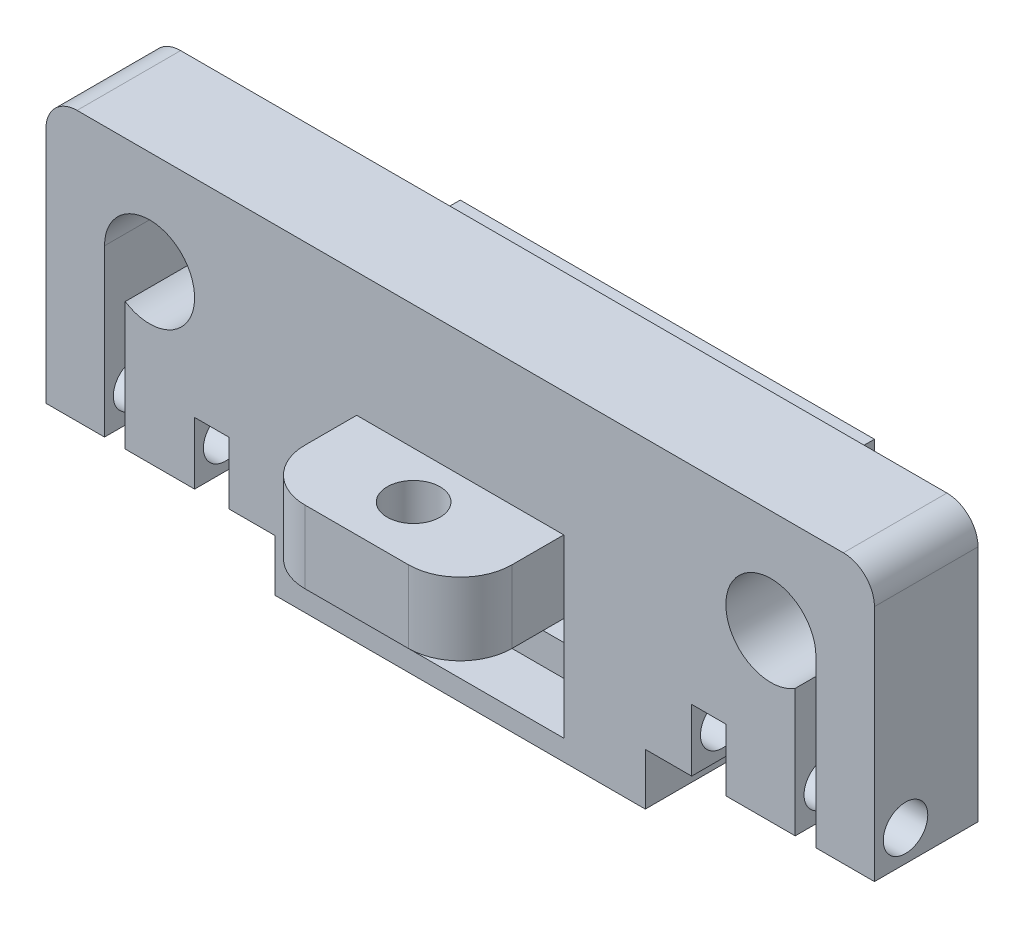
SolidWorks part; units mm, degrees
ref_plane "Front Plane" through (0, 0, 0) normal (0, 0, 1) x (1, 0, 0)
ref_plane "Top Plane" through (0, 0, 0) normal (0, 1, 0) x (1, 0, 0)
ref_plane "Right Plane" through (0, 0, 0) normal (1, 0, 0) x (0, 0, -1)
sketch "Sketch1" plane through (0, 0, 0) normal (0, 0, 1) x (1, 0, 0)
  line L0 (0, -16.0288) -> (0, 16.9064) construction
  line L1 (40, -13) -> (34.35, -13)
  line L2 (40, -13) -> (40, 13)
  line L3 (40, 13) -> (-40, 13)
  line L4 (-40, -13) -> (-40, 13)
  line L5 (40, -13) -> (34.35, -11.1638) construction
  line L6 (40, 13) -> (-32.35, -10.5138) construction
  line L7 (5.1, -6) -> (5.1, -13)
  line L8 (-7.5, -6) -> (-5.1, -6)
  line L9 (-7.5, -6) -> (-7.5, -13)
  line L11 (-5.1, -6) -> (-5.1, -13)
  line L12 (-7.5, -6) -> (-5.1, -13) construction
  line L13 (-7.5, -13) -> (-5.1, -6) construction
  line L14 (7.5, -6) -> (7.5, -13)
  line L15 (7.5, -6) -> (5.1, -6)
  line L16 (-7.5, -13) -> (-32.35, -13)
  line L17 (5.1, -13) -> (-5.1, -13)
  line L18 (-34.35, -13) -> (-40, -13)
  line L20 (-34.35, 3) -> (-34.35, -13)
  line L22 (-32.35, -0.6606) -> (-32.35, -13)
  line L23 (-34.35, -11.1638) -> (-40, -13) construction
  line L24 (32.35, -0.6606) -> (32.35, -13)
  line L25 (34.35, 3) -> (34.35, -13)
  line L26 (32.35, -13) -> (7.5, -13)
  line L27 (32.35, -10.5137) -> (-40, 13) construction
  arc A0 (-32.35, -0.6606) -> (-34.35, 3) centre (-30, 3) ccw
  arc A2 (32.35, -0.6606) -> (34.35, 3) centre (30, 3) cw
  point P0 (0, 0)
  point P13 (-6.3, -9.5)
  point P31 (-32.35, -6.8303)
  dimension "D3" = 8.7
  dimension "D1" = 80
  dimension "D2" = 26
  dimension "D4" = 10
  dimension "D5" = 10
  dimension "D6" = 7
  dimension "D7" = 2.4
  dimension "D8" = 6.3
  dimension "D9" = 2
extrude "Boss-Extrude1" add sketch "Sketch1" along normal mid plane 10
sketch "Sketch2" plane through (0, 0, 5) normal (0, 0, 1) x (1, 0, 0)
  line L5 (-40, 13) -> (-40, -13) construction
  line L6 (-25.65, -13) -> (-22.35, -13)
  line L7 (-25.65, -13) -> (-25.65, -7)
  line L8 (-25.65, -7) -> (-22.35, -7)
  line L9 (-22.35, -13) -> (-22.35, -7)
  line L10 (-25.65, -13) -> (-22.35, -7) construction
  line L11 (-25.65, -7) -> (-22.35, -13) construction
  line L12 (-32.35, -13) -> (-7.5, -13) construction
  line L13 (0, -16.0948) -> (0, 19.1324) construction
  line L14 (22.35, -13) -> (22.35, -7)
  line L15 (25.65, -13) -> (25.65, -7)
  line L16 (25.65, -7) -> (22.35, -7)
  line L17 (25.65, -13) -> (22.35, -13)
  point P0 (-24, -10)
  point P7 (-24, -13)
  dimension "D1" = 16
  dimension "D2" = 3.3
  dimension "D4" = 0
  dimension "D5" = 3
extrude "Cut-Extrude2" cut sketch "Sketch2" against normal blind 6.5 contours L7 L6 L9 L8 | L17 L14 L16 L15
sketch "Sketch3" plane through (-40, 0, 0) normal (-1, 0, 0) x (0, 0, 1)
  line L0 (5, -13) -> (-5, -13) construction
  line L1 (-5, 13) -> (-5, -13) construction
  circle A0 centre (2, -10) radius 2.15
  dimension "D1" = 4.3
  dimension "D2" = 3
  dimension "D3" = 7
extrude "Cut-Extrude4" cut sketch "Sketch3" against normal blind 24
mirror "Mirror1" about plane through (0, 0, 0) normal (1, 0, 0) of "Cut-Extrude4"
fillet "Fillet1" radius 0.5 2 edges at (5.1, -9.5, -5) (-5.1, -9.5, -5)
fillet "Fillet2" radius 3 2 edges at (40, 13, 0) (-40, 13, 0)
sketch "Sketch5" plane through (0, 0, 5) normal (0, 0, 1) x (1, 0, 0)
  line L2 (-5.1, -6) -> (5.1, -6)
  line L3 (-5.1, -6) -> (-5.1, -13)
  line L4 (-5.1, -13) -> (5.1, -13)
  line L5 (5.1, -6) -> (5.1, -13)
  line L6 (-5.1, -6) -> (5.1, -13) construction
  line L7 (-5.1, -13) -> (5.1, -6) construction
  point P2 (0, -9.5)
  dimension "D1" = 7
extrude "Cut-Extrude5" cut sketch "Sketch5" against normal through all
sketch "Sketch8" plane through (0, 0, -5) normal (0, 0, -1) x (-1, 0, 0)
  line L6 (32.35, -13) -> (7.5, -13) construction
  line L7 (-10, -6) -> (10, -6)
  line L8 (-10, -6) -> (-10, -13)
  line L9 (-10, -13) -> (10, -13)
  line L10 (10, -6) -> (10, -13)
  line L11 (-10, -6) -> (10, -13) construction
  line L12 (-10, -13) -> (10, -6) construction
  line L13 (-7.5, -6) -> (-7.5, -13) construction
  line L17 (7.5, -13) -> (7.5, -6) construction
  point P0 (0, -9.5)
  dimension "D1" = 20
  dimension "D2" = 2.5
  dimension "D3" = 2.5
  dimension "D4" = 7
extrude "Cut-Extrude6" cut sketch "Sketch8" against normal through all
sketch "Sketch9" plane through (0, 0, 5) normal (0, 0, 1) x (1, 0, 0)
  line L1 (-10, -6) -> (10, -6)
  line L2 (-10, -6) -> (-10, 1)
  line L3 (-10, 1) -> (10, 1)
  line L4 (10, -6) -> (10, 1)
  dimension "D1" = 7
extrude "Boss-Extrude2" add sketch "Sketch9" along normal blind 10
sketch "Sketch10" plane through (0, 1, 0) normal (0, 1, 0) x (1, 0, 0)
  line L3 (-10, -15) -> (10, -15) construction
  circle A0 centre (0, -9.5) radius 2.55
  dimension "D1" = 5.1
  dimension "D2" = 5.5
extrude "Cut-Extrude7" cut sketch "Sketch10" against normal through all
fillet "Fillet3" radius 5 2 edges at (-10, -2.5, 15) (10, -2.5, 15)
sketch "Sketch11" plane through (0, 0, -5) normal (0, 0, -1) x (-1, 0, 0)
  line L0 (10, -6) -> (-10, -6) construction
  line L1 (-20, -6) -> (20, -6)
  line L2 (-20, -6) -> (-20, 4)
  line L3 (-20, 4) -> (20, 4)
  line L4 (20, -6) -> (20, 4)
  point P1 (0, 0)
  dimension "D1" = 40
  dimension "D2" = 10
  dimension "D3" = 10
extrude "Boss-Extrude3" add sketch "Sketch11" along normal blind 10
sketch "Sketch13" plane through (0, -13, 0) normal (0, -1, 0) x (1, 0, 0)
  line L0 (10, -5) -> (32.35, -5) construction
  line L1 (-17.8714, 5) -> (17.8714, 5)
  line L2 (-17.8714, 5) -> (-17.8714, -5)
  line L3 (-17.8714, -5) -> (17.8714, -5)
  line L4 (17.8714, 5) -> (17.8714, -5)
  line L7 (-22.35, 5) -> (-10, 5) construction
  line L8 (-32.35, -5) -> (-10, -5) construction
  point P0 (0, 0)
extrude "Boss-Extrude5" add sketch "Sketch13" along normal blind 5
sketch "Sketch14" plane through (0, -6, 0) normal (0, -1, 0) x (1, 0, 0)
  line L0 (-20, -15) -> (-20, -5) construction
  line L1 (20, -15) -> (-20, -15) construction
  circle A0 centre (-15, -10) radius 1.4
  circle A1 centre (15, -10) radius 1.4
  dimension "D1" = 2.8
  dimension "D5" = 2.8
  dimension "D2" = 5
  dimension "D3" = 5
  dimension "D4" = 30
extrude "Cut-Extrude8" cut sketch "Sketch14" against normal through all
sketch "Sketch16" plane through (0, 0, 5) normal (0, 0, 1) x (1, 0, 0)
  line L0 (-10, -13) -> (-10, -6) construction
  line L1 (10, -13) -> (-10, -13)
  line L2 (10, -13) -> (10, -16)
  line L3 (10, -16) -> (-10, -16)
  line L4 (-10, -13) -> (-10, -16)
  dimension "D1" = 3
extrude "Cut-Extrude10" cut sketch "Sketch16" against normal blind 5
sketch "Sketch17" plane through (0, -18, 0) normal (0, -1, 0) x (1, 0, 0)
  line L0 (0, -11.6084) -> (0, 16.4008) construction
  line L1 (-17.8714, 5) -> (-17.8714, -5) construction
  circle A0 centre (-13.8714, 0) radius 1
  circle A1 centre (13.8714, 0) radius 1
  dimension "D1" = 2
  dimension "D2" = 4
extrude "Cut-Extrude11" cut sketch "Sketch17" against normal blind 3.5
